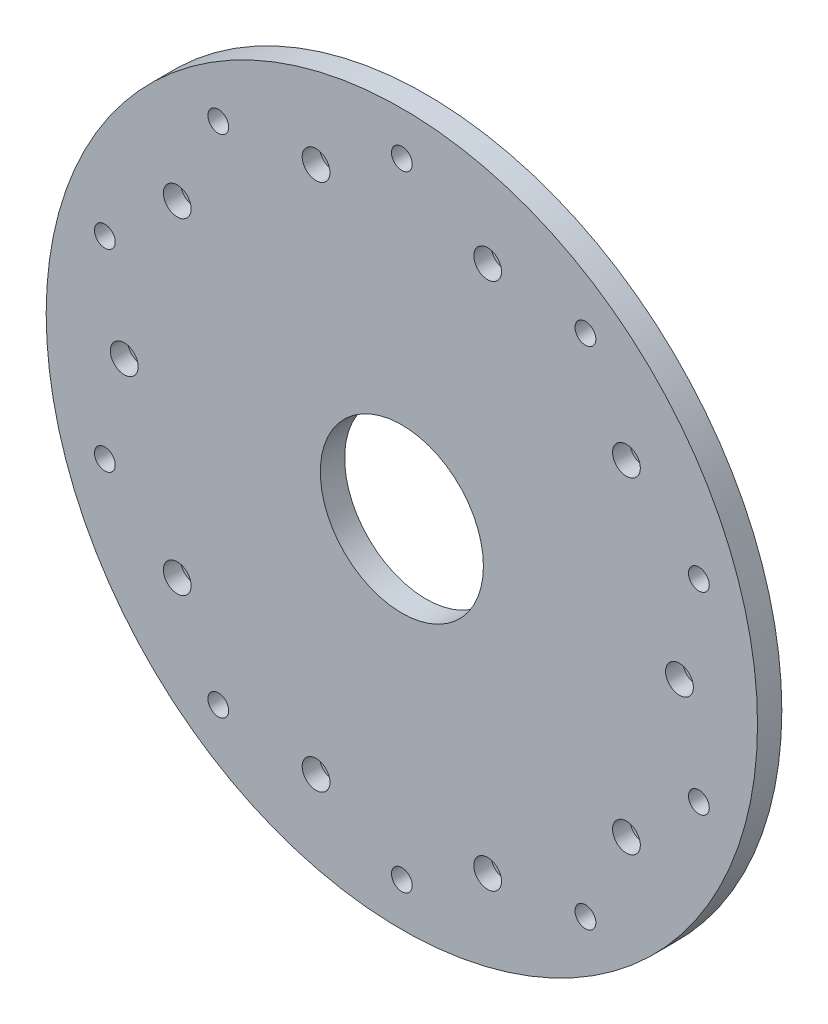
SolidWorks part; units mm, degrees
ref_plane "Front Plane" through (0, 0, 0) normal (0, 0, 1) x (1, 0, 0)
ref_plane "Top Plane" through (0, 0, 0) normal (0, 1, 0) x (1, 0, 0)
ref_plane "Right Plane" through (0, 0, 0) normal (1, 0, 0) x (0, 0, -1)
sketch "Sketch1" plane through (0, 0, 0) normal (0, 0, 1) x (1, 0, 0)
  circle A0 centre (0, 0) radius 102.5
  circle A1 centre (0, 0) radius 23.5
  dimension "D1" = 205
  dimension "D2" = 47
extrude "Boss-Extrude1" add sketch "Sketch1" along normal blind 7
sketch "Sketch2" plane through (0, 0, 7) normal (0, 0, 1) x (1, 0, 0)
  circle A0 centre (0, 90) radius 3
  circle A1 centre (52.9007, 72.8115) radius 3
  circle A2 centre (85.5951, 27.8115) radius 3
  circle A3 centre (85.5951, -27.8115) radius 3
  circle A4 centre (52.9007, -72.8115) radius 3
  circle A5 centre (0, -90) radius 3
  circle A6 centre (-52.9007, -72.8115) radius 3
  circle A7 centre (-85.5951, -27.8115) radius 3
  circle A8 centre (-85.5951, 27.8115) radius 3
  circle A9 centre (-52.9007, 72.8115) radius 3
  point P24 (0, 0)
  dimension "D1" = 6
  dimension "D2" = 90
  dimension "D3" = 10
extrude "Cut-Extrude1" cut sketch "Sketch2" against normal through all
sketch "Sketch3" plane through (0, 0, 7) normal (0, 0, 1) x (1, 0, 0)
  line L0 (0, 0) -> (31.6742, 97.4833) construction
  line L1 (0, 0) -> (0, 102.5)
  circle A0 centre (0, 0) radius 102.5 construction
  circle A1 centre (24.7214, 76.0845) radius 4
  point P9 (24.7214, 76.0845)
  dimension "D3" = 8
  dimension "D1" = 18
  dimension "D2" = 80
extrude "Cut-Extrude2" cut sketch "Sketch3" against normal blind 5 contours A1
pattern_circular "CirPattern1" count 10 over 360 about axis through (0, 0, 0) along (0, 0, 1) of "Cut-Extrude2"
